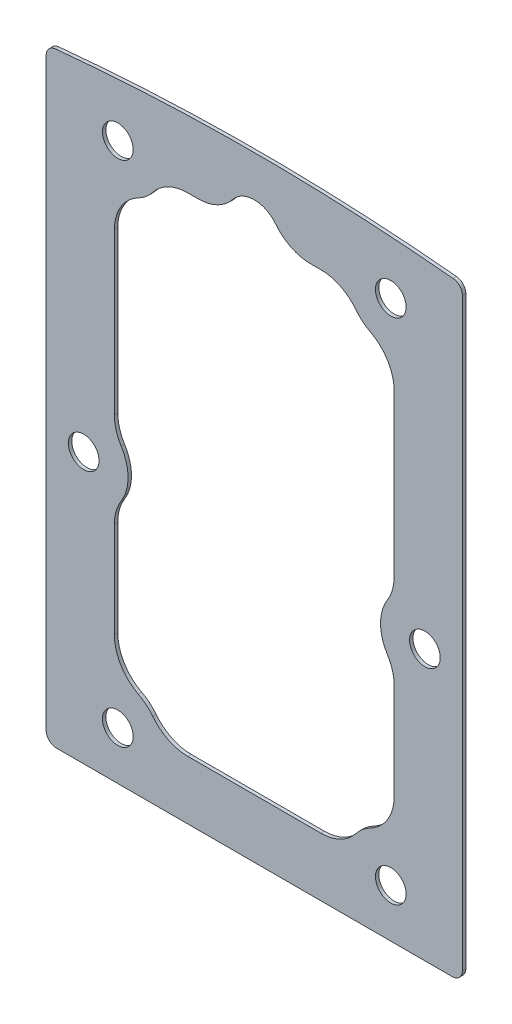
SolidWorks part; units mm, degrees
ref_plane "Front Plane" through (0, 0, 0) normal (0, 0, 1) x (1, 0, 0)
ref_plane "Top Plane" through (0, 0, 0) normal (0, 1, 0) x (1, 0, 0)
ref_plane "Right Plane" through (0, 0, 0) normal (1, 0, 0) x (0, 0, -1)
sketch "Sketch1" plane through (0, 0, 0) normal (0, 0, 1) x (1, 0, 0)
  line L2 (-61, 85.6759) -> (-61, -85.6759)
  line L3 (-58, -88.6759) -> (58, -88.6759)
  line L4 (61, 85.6759) -> (61, -85.6759)
  line L5 (-41, -23.3564) -> (-41, -51.4349)
  line L6 (-41, 51.4349) -> (-41, 4.3564)
  line L8 (-16.4924, 71.5) -> (-19.5061, 71.5)
  line L10 (0, 91.5) -> (0, 79.5) construction
  line L11 (41, -23.3564) -> (41, -51.4349)
  line L12 (-19.5061, -71.5) -> (19.5061, -71.5)
  line L13 (41, 51.4349) -> (41, 4.3564)
  line L14 (16.4924, 71.5) -> (19.5061, 71.5)
  circle A0 centre (-40, 74.5) radius 4.5
  circle A1 centre (-50, -9.5) radius 4.5
  circle A2 centre (-40, -74.5) radius 4.5
  arc A3 (-58, -88.6759) -> (-61, -85.6759) centre (-58, -85.6759) cw
  arc A6 (58, -88.6759) -> (61, -85.6759) centre (58, -85.6759) ccw
  arc A7 (-29.753, -66.5) -> (-34, -62.9674) centre (-40, -74.5) ccw
  arc A9 (-34, 62.9674) -> (-29.753, 66.5) centre (-40, 74.5) ccw
  arc A10 (-19.5061, 71.5) -> (-29.753, 66.5) centre (-19.5061, 58.5) ccw
  arc A11 (-34, 62.9674) -> (-41, 51.4349) centre (-28, 51.4349) ccw
  arc A12 (-41, 4.3564) -> (-39, -2.5718) centre (-28, 4.3564) ccw
  arc A13 (-39, -16.4282) -> (-41, -23.3564) centre (-28, -23.3564) ccw
  arc A14 (-41, -51.4349) -> (-34, -62.9674) centre (-28, -51.4349) ccw
  arc A15 (-29.753, -66.5) -> (-19.5061, -71.5) centre (-19.5061, -58.5) ccw
  arc A16 (6.2828, 76.4524) -> (-6.2828, 76.4524) centre (0, 71.5) ccw
  arc A17 (-16.4924, 71.5) -> (-6.2828, 76.4524) centre (-16.4924, 84.5) ccw
  arc A18 (-39, -16.4282) -> (-39, -2.5718) centre (-50, -9.5) ccw
  arc A19 (29.753, -66.5) -> (19.5061, -71.5) centre (19.5061, -58.5) cw
  arc A20 (29.753, -66.5) -> (34, -62.9674) centre (40, -74.5) cw
  arc A21 (41, -51.4349) -> (34, -62.9674) centre (28, -51.4349) cw
  arc A22 (39, -16.4282) -> (41, -23.3564) centre (28, -23.3564) cw
  arc A23 (39, -16.4282) -> (39, -2.5718) centre (50, -9.5) cw
  arc A24 (41, 4.3564) -> (39, -2.5718) centre (28, 4.3564) cw
  arc A25 (34, 62.9674) -> (41, 51.4349) centre (28, 51.4349) cw
  arc A26 (34, 62.9674) -> (29.753, 66.5) centre (40, 74.5) cw
  arc A27 (19.5061, 71.5) -> (29.753, 66.5) centre (19.5061, 58.5) cw
  arc A28 (16.4924, 71.5) -> (6.2828, 76.4524) centre (16.4924, 84.5) cw
  arc A29 (58.2915, 88.6617) -> (-58.2915, 88.6617) centre (0, -508.5) ccw
  arc A30 (-58.2915, 88.6617) -> (-61, 85.6759) centre (-58, 85.6759) ccw
  arc A31 (61, 85.6759) -> (58.2915, 88.6617) centre (58, 85.6759) ccw
  circle A32 centre (40, -74.5) radius 4.5
  circle A33 centre (50, -9.5) radius 4.5
  circle A34 centre (40, 74.5) radius 4.5
  point P6 (61, 0)
  point P17 (-61, -88.6759)
  point P20 (61, 94.3241)
  point P23 (-61, 94.3241)
  dimension "D3" = 9
  dimension "D12" = 3
  dimension "D17" = 16
  dimension "D7" = 600
  dimension "D1" = 122
  dimension "D2" = 183
  dimension "D9" = 84
  dimension "D11" = 65
  dimension "D15" = 20
extrude "Boss-Extrude1" add sketch "Sketch1" along normal blind 1
